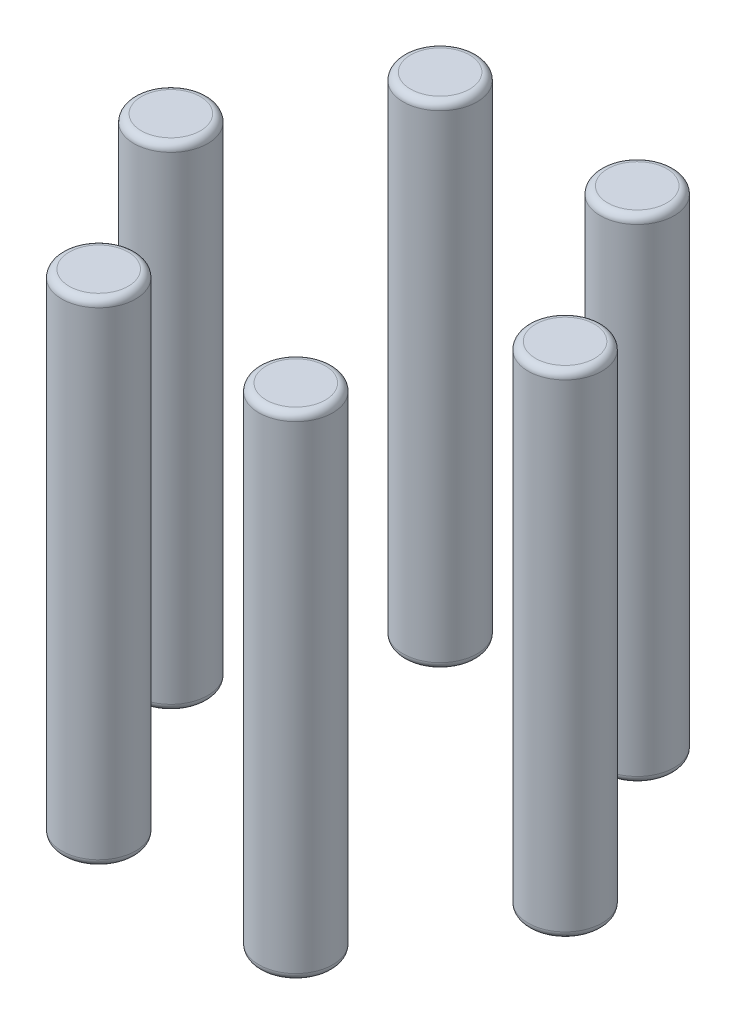
SolidWorks part; units mm, degrees
ref_plane "Front Plane" through (0, 0, 0) normal (0, 0, 1) x (1, 0, 0)
ref_plane "Top Plane" through (0, 0, 0) normal (0, 1, 0) x (1, 0, 0)
ref_plane "Right Plane" through (0, 0, 0) normal (1, 0, 0) x (0, 0, -1)
sketch "Sketch1" plane through (0, 0, 0) normal (0, 1, 0) x (1, 0, 0)
  line L0 (-15.4, 0) -> (14.4, 0) construction
  line L1 (0, 0) -> (0, -14.9128) construction
  line L2 (0, 0) -> (0, 14.9128) construction
  line L3 (-0.5, 0) -> (-0.5, -14.9128) construction
  line L4 (-0.5, 0) -> (-0.5, 14.9128) construction
  line L5 (14.4, 0) -> (15.5, 0) construction
  line L6 (0, 14.9128) -> (0, -14.9128) construction
  line L7 (5.9, 0) -> (9.1, 0) construction
  line L8 (5.9, 0) -> (7.5, 0)
  circle A0 centre (-0.5, 0) radius 16 construction
  circle A1 centre (15.5, 0) radius 1
  circle A2 centre (15.0351, -3.8291) radius 1
  circle A3 centre (13.6673, -7.4356) radius 1
  circle A4 centre (11.4762, -10.61) radius 1
  circle A5 centre (8.589, -13.1677) radius 1
  circle A6 centre (5.1737, -14.9603) radius 1
  circle A7 centre (1.4286, -15.8833) radius 1
  circle A8 centre (-2.4286, -15.8833) radius 1
  circle A9 centre (-6.1737, -14.9603) radius 1
  circle A10 centre (-9.589, -13.1677) radius 1
  circle A11 centre (-12.4762, -10.61) radius 1
  circle A12 centre (-14.6673, -7.4356) radius 1
  circle A13 centre (-16.0351, -3.8291) radius 1
  circle A14 centre (-16.5, 0) radius 1
  circle A15 centre (-16.0351, 3.8291) radius 1
  circle A16 centre (-14.6673, 7.4356) radius 1
  circle A17 centre (-12.4762, 10.61) radius 1
  circle A18 centre (-9.589, 13.1677) radius 1
  circle A19 centre (-6.1737, 14.9603) radius 1
  circle A20 centre (-2.4286, 15.8833) radius 1
  circle A21 centre (1.4286, 15.8833) radius 1
  circle A22 centre (5.1737, 14.9603) radius 1
  circle A23 centre (8.589, 13.1677) radius 1
  circle A24 centre (11.4762, 10.61) radius 1
  circle A25 centre (13.6673, 7.4356) radius 1
  circle A26 centre (15.0351, 3.8291) radius 1
  circle A27 centre (0, 0) radius 8
  circle A28 centre (8, 0) radius 2.1
  circle A29 centre (4, 6.9282) radius 2.1
  circle A30 centre (-4, 6.9282) radius 2.1
  circle A31 centre (-8, 0) radius 2.1
  circle A32 centre (-4, -6.9282) radius 2.1
  circle A33 centre (4, -6.9282) radius 2.1
  circle A34 centre (-1, 0) radius 8 construction
  circle A35 centre (3, -6.9282) radius 2.1
  circle A36 centre (-5, -6.9282) radius 2.1
  circle A37 centre (-9, 0) radius 2.1
  circle A38 centre (-5, 6.9282) radius 2.1
  circle A39 centre (3, 6.9282) radius 2.1
  circle A40 centre (7, 0) radius 2.1
  circle A41 centre (7.5, 0) radius 1.5
  circle A42 centre (3.5, -6.9282) radius 1.5
  circle A43 centre (-4.5, -6.9282) radius 1.5
  circle A44 centre (-8.5, 0) radius 1.5
  circle A45 centre (-4.5, 6.9282) radius 1.5
  circle A46 centre (3.5, 6.9282) radius 1.5
  spline S0 degree 4 poles (14.1521, 3.1658) (14.188, 3.1199) (14.2658, 3.0332) (14.3775, 2.9384) (14.515, 2.8555) (14.6203, 2.806) (14.6874, 2.778) (14.7412, 2.7556) (14.7939, 2.7309) (14.8442, 2.7016) (14.9616, 2.6171) (15.116, 2.4418) (15.2531, 2.163) (15.3044, 1.8261) (15.2781, 1.5454) (15.2134, 1.3341) (15.1457, 1.199) (15.0717, 1.0959) (14.999, 1.0246) (14.9346, 0.9749) (14.8529, 0.9144) (14.7598, 0.8351) (14.6613, 0.7318) (14.5658, 0.5985) (14.4899, 0.4547) (14.4445, 0.3242) (14.4198, 0.2202) (14.4058, 0.1237) (14.3997, 0.036) (14.399, -0.0233) (14.4055, -0.1232) (14.4175, -0.2057) (14.4353, -0.2848) (14.4589, -0.3638) (14.4955, -0.4601) (14.5538, -0.5777) (14.629, -0.6905) (14.7205, -0.7952) (14.8099, -0.8785) (14.886, -0.9397) (14.9653, -0.9969) (15.0394, -1.0608) (15.1018, -1.1365) (15.1543, -1.2193) (15.2086, -1.3292) (15.2563, -1.4688) (15.2881, -1.6381) (15.2945, -1.881) (15.2523, -2.1199) (15.1638, -2.3444) (15.0424, -2.5231) (14.9425, -2.6287) (14.8453, -2.7036) (14.7572, -2.7504) (14.6644, -2.7867) (14.5734, -2.827) (14.4636, -2.8857) (14.309, -2.9902) (14.1305, -3.1658) (13.9721, -3.435) (13.894, -3.7733) (13.9169, -4.0803) (13.9952, -4.3102) (14.0824, -4.4685) (14.1503, -4.5677) (14.21, -4.6429) (14.2706, -4.7176) (14.3202, -4.8002) (14.3654, -4.9109) (14.3993, -5.0496) (14.4169, -5.2624) (14.3843, -5.5009) (14.3041, -5.731) (14.178, -5.9418) (14.0479, -6.0957) (13.9108, -6.2086) (13.7771, -6.2844) (13.6546, -6.3259) (13.5506, -6.3413) (13.4467, -6.3556) (13.3441, -6.3782) (13.2186, -6.4164) (13.0491, -6.4902) (12.8504, -6.6239) (12.6494, -6.8484) (12.5061, -7.1523) (12.463, -7.451) (12.49, -7.6921) (12.5392, -7.8624) (12.5803, -7.968) (12.6183, -8.0504) (12.6544, -8.1336) (12.6783, -8.2214) (12.6929, -8.336) (12.6907, -8.4762) (12.6543, -8.6855) (12.5452, -8.9512) (12.3731, -9.1837) (12.1492, -9.3663) (11.9533, -9.4633) (11.8116, -9.5062) (11.6867, -9.5225) (11.5835, -9.517) (11.4812, -9.5034) (11.3782, -9.4969) (11.2749, -9.4982) (11.1721, -9.508) (11.0085, -9.5382) (10.791, -9.6158) (10.5438, -9.7787) (10.3474, -10.0243) (10.2402, -10.2686) (10.1943, -10.4842) (10.1853, -10.6384) (10.1931, -10.7705) (10.2091, -10.8795) (10.2256, -10.9662) (10.236, -11.0539) (10.2331, -11.1423) (10.2158, -11.2534) (10.1767, -11.3842) (10.0886, -11.5718) (9.9146, -11.8006) (9.6439, -12.0158) (9.3384, -12.1314) (9.0923, -12.1519) (8.9388, -12.1247) (8.8741, -12.1049) (8.8233, -12.0863) (8.76, -12.0622) (8.6577, -12.0268) (8.5127, -11.9913) (8.2954, -11.971) (8.0233, -12.0058) (7.7397, -12.12) (7.4775, -12.3303) (7.3093, -12.5758) (7.2277, -12.7964) (7.1948, -12.9647) (7.1831, -13.0729) (7.1774, -13.16) (7.1639, -13.2682) (7.1207, -13.3961) (7.0432, -13.5357) (6.8963, -13.7154) (6.6678, -13.8963) (6.3478, -14.0387) (6.02, -14.0727) (5.7619, -14.0269) (5.5985, -13.9438) (5.5126, -13.8801) (5.4018, -13.8057) (5.2599, -13.7303) (5.0524, -13.6565) (4.7738, -13.623) (4.4626, -13.6683) (4.1888, -13.7999) (3.9912, -13.9665) (3.8578, -14.1339) (3.7826, -14.2632) (3.7309, -14.3799) (3.6959, -14.48) (3.6689, -14.5606) (3.6251, -14.6573) (3.5494, -14.7647) (3.44, -14.8752) (3.2557, -15.006) (2.9928, -15.1201) (2.6515, -15.1757) (2.3406, -15.1291) (2.1258, -15.0338) (2.011, -14.9468) (1.9698, -14.909) (1.9317, -14.8681) (1.8954, -14.8255) (1.8499, -14.7726) (1.7735, -14.691) (1.6576, -14.5893) (1.4677, -14.4687) (1.2013, -14.3748) (0.8943, -14.3518) (0.5705, -14.4236) (0.3173, -14.5632) (0.1515, -14.7141) (0.0481, -14.8418) (-0.0114, -14.9289) (-0.057, -15.0001) (-0.1205, -15.0845) (-0.2167, -15.1711) (-0.3455, -15.2521) (-0.5484, -15.3356) (-0.8128, -15.3854) (-1.084, -15.3726) (-1.345, -15.2972) (-1.5435, -15.1922) (-1.6658, -15.0976) (-1.7547, -15.002) (-1.8112, -14.9128) (-1.8483, -14.8369) (-1.8948, -14.7422) (-1.9811, -14.5964) (-2.1305, -14.4153) (-2.3717, -14.2374) (-2.6941, -14.1243) (-3.0058, -14.1121) (-3.2798, -14.1742) (-3.4814, -14.2713) (-3.6077, -14.3581) (-3.6929, -14.4296) (-3.7443, -14.4763) (-3.7855, -14.5136) (-3.839, -14.5578) (-3.9718, -14.6426) (-4.2092, -14.7163) (-4.5379, -14.7232) (-4.871, -14.6233) (-5.1192, -14.4741) (-5.2872, -14.3161) (-5.3818, -14.1888) (-5.4416, -14.0686) (-5.4698, -13.9639) (-5.4862, -13.8788) (-5.5106, -13.7734) (-5.5628, -13.6112) (-5.6686, -13.4029) (-5.8615, -13.1808) (-6.1409, -13.0036) (-6.4324, -12.9205) (-6.707, -12.9139) (-6.9246, -12.958) (-7.0705, -13.0119) (-7.1719, -13.0612) (-7.2342, -13.0943) (-7.2842, -13.1203) (-7.3485, -13.1494) (-7.4504, -13.1813) (-7.5929, -13.1993) (-7.8225, -13.1875) (-8.1082, -13.1019) (-8.3607, -12.9481) (-8.5641, -12.7393) (-8.6869, -12.541) (-8.7459, -12.3913) (-8.7711, -12.2579) (-8.7697, -12.1482) (-8.7645, -12.0606) (-8.7633, -11.951) (-8.7731, -11.8212) (-8.8019, -11.6732) (-8.8729, -11.4717) (-9.0045, -11.25) (-9.2205, -11.0351) (-9.4997, -10.8905) (-9.7475, -10.8369) (-9.9383, -10.8322) (-10.0675, -10.8437) (-10.1698, -10.8609) (-10.2704, -10.8859) (-10.3717, -10.9089) (-10.4995, -10.9144) (-10.6499, -10.893) (-10.8644, -10.8236) (-11.1154, -10.6702) (-11.3185, -10.4608) (-11.4614, -10.2119) (-11.5248, -10.0134) (-11.5464, -9.8777) (-11.5487, -9.7646) (-11.5393, -9.6761) (-11.5169, -9.5902) (-11.4896, -9.5058) (-11.4606, -9.3988) (-11.4371, -9.2678) (-11.428, -9.1126) (-11.4489, -8.8917) (-11.5253, -8.6444) (-11.6806, -8.3917) (-11.9083, -8.1893) (-12.1461, -8.0664) (-12.3515, -8.0112) (-12.509, -7.9918) (-12.6408, -7.9895) (-12.7466, -7.9882) (-12.8744, -7.9638) (-13.0178, -7.9059) (-13.1692, -7.8114) (-13.319, -7.6747) (-13.472, -7.4805) (-13.5815, -7.2609) (-13.644, -7.0266) (-13.6529, -6.8129) (-13.6365, -6.6729) (-13.6064, -6.5605) (-13.5704, -6.4764) (-13.5232, -6.3982) (-13.4752, -6.3206) (-13.4215, -6.2199) (-13.3522, -6.0556) (-13.2972, -5.8178) (-13.3061, -5.5112) (-13.4183, -5.1858) (-13.5996, -4.9373) (-13.7884, -4.7826) (-13.9504, -4.6931) (-14.068, -4.6441) (-14.1647, -4.6121) (-14.2634, -4.587) (-14.3606, -4.5562) (-14.4721, -4.4972) (-14.5906, -4.4054) (-14.7415, -4.2409) (-14.8856, -3.984) (-14.9605, -3.7) (-14.9625, -3.4094) (-14.9171, -3.1994) (-14.8649, -3.0656) (-14.8048, -2.9613) (-14.7437, -2.886) (-14.6735, -2.8194) (-14.6048, -2.7515) (-14.5411, -2.6786) (-14.4829, -2.6013) (-14.3984, -2.4684) (-14.3099, -2.2678) (-14.2572, -1.9916) (-14.2948, -1.6527) (-14.4157, -1.3725) (-14.5648, -1.1806) (-14.7009, -1.0585) (-14.8015, -0.9857) (-14.886, -0.9336) (-14.9732, -0.8861) (-15.056, -0.8309) (-15.1453, -0.7457) (-15.2341, -0.6279) (-15.3021, -0.4979) (-15.3506, -0.3595) (-15.3784, -0.2422) (-15.3932, -0.1473) (-15.4005, -0.038) (-15.4007, 0.0312) (-15.3943, 0.133) (-15.3819, 0.2227) (-15.3632, 0.3082) (-15.3383, 0.3938) (-15.2991, 0.498) (-15.241, 0.614) (-15.1569, 0.7356) (-15.0521, 0.8388) (-14.947, 0.9) (-14.8417, 0.9596) (-14.7374, 1.0292) (-14.6222, 1.1253) (-14.4762, 1.2888) (-14.3483, 1.5104) (-14.2696, 1.788) (-14.2718, 2.0824) (-14.3338, 2.3297) (-14.4228, 2.5131) (-14.5089, 2.6398) (-14.5912, 2.7371) (-14.6628, 2.8095) (-14.7315, 2.8736) (-14.7874, 2.9388) (-14.8392, 3.0187) (-14.9, 3.1445) (-14.933, 3.2628) (-14.9484, 3.3663) (-14.9531, 3.4358) knots 0 0 0 0 0 0.003662 0.007324 0.009155 0.010071 0.010986 0.011902 0.012818 0.013733 0.014649 0.020984 0.02732 0.032959 0.035778 0.038598 0.041156 0.042436 0.043715 0.044995 0.046274 0.048833 0.051398 0.053964 0.05653 0.059096 0.059963 0.060831 0.062566 0.06386 0.065154 0.066448 0.067743 0.069037 0.070331 0.072919 0.075992 0.077529 0.079065 0.080602 0.082139 0.083675 0.085212 0.086754 0.088296 0.09138 0.094464 0.097548 0.103529 0.106519 0.10951 0.111075 0.112641 0.114207 0.115773 0.117339 0.118905 0.122036 0.127492 0.132948 0.138255 0.143562 0.146585 0.148096 0.149608 0.151119 0.15263 0.154142 0.155653 0.158618 0.161583 0.167513 0.170668 0.173824 0.176979 0.180135 0.181785 0.183435 0.185086 0.186736 0.188387 0.190037 0.193338 0.198334 0.203329 0.208757 0.214186 0.217039 0.218465 0.219892 0.221319 0.222745 0.224172 0.225598 0.228568 0.231538 0.237477 0.243509 0.246525 0.249541 0.251164 0.252787 0.25441 0.256033 0.257656 0.259279 0.260902 0.262525 0.268116 0.273708 0.279232 0.281995 0.284757 0.287531 0.288919 0.290306 0.291693 0.293081 0.294468 0.295855 0.298752 0.301648 0.307441 0.313806 0.320171 0.321875 0.322726 0.323578 0.32443 0.325282 0.326985 0.330392 0.333799 0.338942 0.344084 0.349371 0.354658 0.3574 0.358771 0.360142 0.361513 0.362884 0.365627 0.368572 0.371516 0.377406 0.383828 0.390249 0.39193 0.393611 0.395291 0.396972 0.400333 0.403695 0.409076 0.414457 0.419833 0.422521 0.425209 0.427878 0.429213 0.430548 0.431883 0.433218 0.435887 0.438758 0.441629 0.44737 0.453781 0.460191 0.46107 0.46195 0.462829 0.463708 0.464587 0.465466 0.467225 0.470742 0.474259 0.479542 0.484825 0.489836 0.494847 0.497504 0.498832 0.500161 0.501489 0.502818 0.505475 0.508247 0.51102 0.516564 0.52227 0.525123 0.527976 0.530631 0.531959 0.533286 0.534614 0.535941 0.538597 0.543936 0.549276 0.554531 0.559787 0.563284 0.566782 0.568531 0.569405 0.570279 0.571154 0.572028 0.573777 0.580153 0.586529 0.592383 0.595311 0.598238 0.600963 0.602326 0.603688 0.605051 0.606414 0.609139 0.614393 0.619646 0.62466 0.629675 0.633224 0.636772 0.638547 0.639434 0.640321 0.641208 0.642095 0.64387 0.647026 0.650182 0.656494 0.66242 0.665383 0.668345 0.671105 0.672484 0.673864 0.675243 0.676623 0.679382 0.682041 0.684701 0.690021 0.695473 0.700926 0.704188 0.705819 0.70745 0.709081 0.710712 0.712344 0.713975 0.717095 0.720216 0.726458 0.732287 0.735201 0.738116 0.739511 0.740907 0.742302 0.743698 0.745093 0.746488 0.749279 0.752059 0.754839 0.760398 0.765424 0.770449 0.773769 0.777088 0.778748 0.780408 0.782068 0.783727 0.786901 0.790075 0.793249 0.796422 0.802397 0.805385 0.808372 0.809808 0.811244 0.812679 0.814115 0.81555 0.816986 0.819857 0.825318 0.830779 0.83599 0.841201 0.844404 0.846006 0.847607 0.849209 0.850811 0.852412 0.854014 0.857107 0.8602 0.866387 0.872353 0.875336 0.878319 0.87984 0.881361 0.882882 0.884402 0.885923 0.887444 0.888965 0.890486 0.895823 0.90116 0.906397 0.911634 0.914757 0.916319 0.91788 0.919441 0.921003 0.922564 0.924126 0.927182 0.930238 0.931767 0.933295 0.934823 0.936351 0.937751 0.93915 0.940549 0.941949 0.943348 0.944747 0.947546 0.950087 0.952628 0.953898 0.955168 0.957709 0.960509 0.96331 0.96891 0.973663 0.978415 0.981621 0.984826 0.986428 0.988031 0.989634 0.991236 0.992332 0.993427 0.995618 1 1 1 1 1 construction
  spline S1 degree 4 poles (14.4, 0) (14.4, -0.018) (14.401, -0.0542) (14.4055, -0.1232) (14.4175, -0.2057) (14.4353, -0.2848) (14.4589, -0.3638) (14.4955, -0.4601) (14.5538, -0.5777) (14.629, -0.6905) (14.7205, -0.7952) (14.8099, -0.8785) (14.886, -0.9397) (14.9653, -0.9969) (15.0394, -1.0608) (15.1018, -1.1365) (15.1543, -1.2193) (15.2086, -1.3292) (15.2563, -1.4688) (15.2881, -1.6381) (15.2945, -1.881) (15.2523, -2.1199) (15.1638, -2.3444) (15.0424, -2.5231) (14.9425, -2.6287) (14.8453, -2.7036) (14.7572, -2.7504) (14.6644, -2.7867) (14.5734, -2.827) (14.4636, -2.8857) (14.309, -2.9902) (14.1305, -3.1658) (13.9721, -3.435) (13.894, -3.7733) (13.9169, -4.0803) (13.9952, -4.3102) (14.0824, -4.4685) (14.1503, -4.5677) (14.21, -4.6429) (14.2706, -4.7176) (14.3202, -4.8002) (14.3654, -4.9109) (14.3993, -5.0496) (14.4169, -5.2624) (14.3843, -5.5009) (14.3041, -5.731) (14.178, -5.9418) (14.0479, -6.0957) (13.9108, -6.2086) (13.7771, -6.2844) (13.6546, -6.3259) (13.5506, -6.3413) (13.4467, -6.3556) (13.3441, -6.3782) (13.2186, -6.4164) (13.0491, -6.4902) (12.8504, -6.6239) (12.6494, -6.8484) (12.5061, -7.1523) (12.463, -7.451) (12.49, -7.6921) (12.5392, -7.8624) (12.5803, -7.968) (12.6183, -8.0504) (12.6544, -8.1336) (12.6783, -8.2214) (12.6929, -8.336) (12.6907, -8.4762) (12.6543, -8.6855) (12.5452, -8.9512) (12.3731, -9.1837) (12.1492, -9.3663) (11.9533, -9.4633) (11.8116, -9.5062) (11.6867, -9.5225) (11.5835, -9.517) (11.4812, -9.5034) (11.3782, -9.4969) (11.2749, -9.4982) (11.1721, -9.508) (11.0085, -9.5382) (10.791, -9.6158) (10.5438, -9.7787) (10.3474, -10.0243) (10.2402, -10.2686) (10.1943, -10.4842) (10.1853, -10.6384) (10.1931, -10.7705) (10.2091, -10.8795) (10.2256, -10.9662) (10.236, -11.0539) (10.2331, -11.1423) (10.2158, -11.2534) (10.1767, -11.3842) (10.0886, -11.5718) (9.9146, -11.8006) (9.6439, -12.0158) (9.3384, -12.1314) (9.0923, -12.1519) (8.9388, -12.1247) (8.8741, -12.1049) (8.8233, -12.0863) (8.76, -12.0622) (8.6577, -12.0268) (8.5127, -11.9913) (8.2954, -11.971) (8.0233, -12.0058) (7.7397, -12.12) (7.4775, -12.3303) (7.3093, -12.5758) (7.2277, -12.7964) (7.1948, -12.9647) (7.1831, -13.0729) (7.1774, -13.16) (7.1639, -13.2682) (7.1207, -13.3961) (7.0432, -13.5357) (6.8963, -13.7154) (6.6678, -13.8963) (6.3478, -14.0387) (6.02, -14.0727) (5.7619, -14.0269) (5.5985, -13.9438) (5.5126, -13.8801) (5.4018, -13.8057) (5.2599, -13.7303) (5.0524, -13.6565) (4.7738, -13.623) (4.4626, -13.6683) (4.1888, -13.7999) (3.9912, -13.9665) (3.8578, -14.1339) (3.7826, -14.2632) (3.7309, -14.3799) (3.6959, -14.48) (3.6689, -14.5606) (3.6251, -14.6573) (3.5494, -14.7647) (3.44, -14.8752) (3.2557, -15.006) (2.9928, -15.1201) (2.6515, -15.1757) (2.3406, -15.1291) (2.1258, -15.0338) (2.011, -14.9468) (1.9698, -14.909) (1.9317, -14.8681) (1.8954, -14.8255) (1.8499, -14.7726) (1.7735, -14.691) (1.6576, -14.5893) (1.4677, -14.4687) (1.2013, -14.3748) (0.8943, -14.3518) (0.5705, -14.4236) (0.3173, -14.5632) (0.1515, -14.7141) (0.0481, -14.8418) (-0.0114, -14.9289) (-0.057, -15.0001) (-0.1205, -15.0845) (-0.2167, -15.1711) (-0.3455, -15.2521) (-0.5484, -15.3356) (-0.8128, -15.3854) (-1.084, -15.3726) (-1.345, -15.2972) (-1.5435, -15.1922) (-1.6658, -15.0976) (-1.7547, -15.002) (-1.8112, -14.9128) (-1.8483, -14.8369) (-1.8948, -14.7422) (-1.9811, -14.5964) (-2.1305, -14.4153) (-2.3717, -14.2374) (-2.6941, -14.1243) (-3.0058, -14.1121) (-3.2798, -14.1742) (-3.4814, -14.2713) (-3.6077, -14.3581) (-3.6929, -14.4296) (-3.7443, -14.4763) (-3.7855, -14.5136) (-3.839, -14.5578) (-3.9718, -14.6426) (-4.2092, -14.7163) (-4.5379, -14.7232) (-4.871, -14.6233) (-5.1192, -14.4741) (-5.2872, -14.3161) (-5.3818, -14.1888) (-5.4416, -14.0686) (-5.4698, -13.9639) (-5.4862, -13.8788) (-5.5106, -13.7734) (-5.5628, -13.6112) (-5.6686, -13.4029) (-5.8615, -13.1808) (-6.1409, -13.0036) (-6.4324, -12.9205) (-6.707, -12.9139) (-6.9246, -12.958) (-7.0705, -13.0119) (-7.1719, -13.0612) (-7.2342, -13.0943) (-7.2842, -13.1203) (-7.3485, -13.1494) (-7.4504, -13.1813) (-7.5929, -13.1993) (-7.8225, -13.1875) (-8.1082, -13.1019) (-8.3607, -12.9481) (-8.5641, -12.7393) (-8.6869, -12.541) (-8.7459, -12.3913) (-8.7711, -12.2579) (-8.7697, -12.1482) (-8.7645, -12.0606) (-8.7633, -11.951) (-8.7731, -11.8212) (-8.8019, -11.6732) (-8.8729, -11.4717) (-9.0045, -11.25) (-9.2205, -11.0351) (-9.4997, -10.8905) (-9.7475, -10.8369) (-9.9383, -10.8322) (-10.0675, -10.8437) (-10.1698, -10.8609) (-10.2704, -10.8859) (-10.3717, -10.9089) (-10.4995, -10.9144) (-10.6499, -10.893) (-10.8644, -10.8236) (-11.1154, -10.6702) (-11.3185, -10.4608) (-11.4614, -10.2119) (-11.5248, -10.0134) (-11.5464, -9.8777) (-11.5487, -9.7646) (-11.5393, -9.6761) (-11.5169, -9.5902) (-11.4896, -9.5058) (-11.4606, -9.3988) (-11.4371, -9.2678) (-11.428, -9.1126) (-11.4489, -8.8917) (-11.5253, -8.6444) (-11.6806, -8.3917) (-11.9083, -8.1893) (-12.1461, -8.0664) (-12.3515, -8.0112) (-12.509, -7.9918) (-12.6408, -7.9895) (-12.7466, -7.9882) (-12.8744, -7.9638) (-13.0178, -7.9059) (-13.1692, -7.8114) (-13.319, -7.6747) (-13.472, -7.4805) (-13.5815, -7.2609) (-13.644, -7.0266) (-13.6529, -6.8129) (-13.6365, -6.6729) (-13.6064, -6.5605) (-13.5704, -6.4764) (-13.5232, -6.3982) (-13.4752, -6.3206) (-13.4215, -6.2199) (-13.3522, -6.0556) (-13.2972, -5.8178) (-13.3061, -5.5112) (-13.4183, -5.1858) (-13.5996, -4.9373) (-13.7884, -4.7826) (-13.9504, -4.6931) (-14.068, -4.6441) (-14.1647, -4.6121) (-14.2634, -4.587) (-14.3606, -4.5562) (-14.4721, -4.4972) (-14.5906, -4.4054) (-14.7415, -4.2409) (-14.8856, -3.984) (-14.9605, -3.7) (-14.9625, -3.4094) (-14.9171, -3.1994) (-14.8649, -3.0656) (-14.8048, -2.9613) (-14.7437, -2.886) (-14.6735, -2.8194) (-14.6048, -2.7515) (-14.5411, -2.6786) (-14.4829, -2.6013) (-14.3984, -2.4684) (-14.3099, -2.2678) (-14.2572, -1.9916) (-14.2948, -1.6527) (-14.4157, -1.3725) (-14.5648, -1.1806) (-14.7009, -1.0585) (-14.8015, -0.9857) (-14.886, -0.9336) (-14.9732, -0.8861) (-15.056, -0.8309) (-15.1453, -0.7457) (-15.2341, -0.6279) (-15.3021, -0.4979) (-15.3506, -0.3595) (-15.3784, -0.2422) (-15.3932, -0.1473) (-15.3988, -0.0635) (-15.4, -0.0212) (-15.4, 0) knots 0.062566 0.062566 0.062566 0.062566 0.062566 0.06386 0.065154 0.066448 0.067743 0.069037 0.070331 0.072919 0.075992 0.077529 0.079065 0.080602 0.082139 0.083675 0.085212 0.086754 0.088296 0.09138 0.094464 0.097548 0.103529 0.106519 0.10951 0.111075 0.112641 0.114207 0.115773 0.117339 0.118905 0.122036 0.127492 0.132948 0.138255 0.143562 0.146585 0.148096 0.149608 0.151119 0.15263 0.154142 0.155653 0.158618 0.161583 0.167513 0.170668 0.173824 0.176979 0.180135 0.181785 0.183435 0.185086 0.186736 0.188387 0.190037 0.193338 0.198334 0.203329 0.208757 0.214186 0.217039 0.218465 0.219892 0.221319 0.222745 0.224172 0.225598 0.228568 0.231538 0.237477 0.243509 0.246525 0.249541 0.251164 0.252787 0.25441 0.256033 0.257656 0.259279 0.260902 0.262525 0.268116 0.273708 0.279232 0.281995 0.284757 0.287531 0.288919 0.290306 0.291693 0.293081 0.294468 0.295855 0.298752 0.301648 0.307441 0.313806 0.320171 0.321875 0.322726 0.323578 0.32443 0.325282 0.326985 0.330392 0.333799 0.338942 0.344084 0.349371 0.354658 0.3574 0.358771 0.360142 0.361513 0.362884 0.365627 0.368572 0.371516 0.377406 0.383828 0.390249 0.39193 0.393611 0.395291 0.396972 0.400333 0.403695 0.409076 0.414457 0.419833 0.422521 0.425209 0.427878 0.429213 0.430548 0.431883 0.433218 0.435887 0.438758 0.441629 0.44737 0.453781 0.460191 0.46107 0.46195 0.462829 0.463708 0.464587 0.465466 0.467225 0.470742 0.474259 0.479542 0.484825 0.489836 0.494847 0.497504 0.498832 0.500161 0.501489 0.502818 0.505475 0.508247 0.51102 0.516564 0.52227 0.525123 0.527976 0.530631 0.531959 0.533286 0.534614 0.535941 0.538597 0.543936 0.549276 0.554531 0.559787 0.563284 0.566782 0.568531 0.569405 0.570279 0.571154 0.572028 0.573777 0.580153 0.586529 0.592383 0.595311 0.598238 0.600963 0.602326 0.603688 0.605051 0.606414 0.609139 0.614393 0.619646 0.62466 0.629675 0.633224 0.636772 0.638547 0.639434 0.640321 0.641208 0.642095 0.64387 0.647026 0.650182 0.656494 0.66242 0.665383 0.668345 0.671105 0.672484 0.673864 0.675243 0.676623 0.679382 0.682041 0.684701 0.690021 0.695473 0.700926 0.704188 0.705819 0.70745 0.709081 0.710712 0.712344 0.713975 0.717095 0.720216 0.726458 0.732287 0.735201 0.738116 0.739511 0.740907 0.742302 0.743698 0.745093 0.746488 0.749279 0.752059 0.754839 0.760398 0.765424 0.770449 0.773769 0.777088 0.778748 0.780408 0.782068 0.783727 0.786901 0.790075 0.793249 0.796422 0.802397 0.805385 0.808372 0.809808 0.811244 0.812679 0.814115 0.81555 0.816986 0.819857 0.825318 0.830779 0.83599 0.841201 0.844404 0.846006 0.847607 0.849209 0.850811 0.852412 0.854014 0.857107 0.8602 0.866387 0.872353 0.875336 0.878319 0.87984 0.881361 0.882882 0.884402 0.885923 0.887444 0.888965 0.890486 0.895823 0.90116 0.906397 0.911634 0.914757 0.916319 0.91788 0.919441 0.921003 0.922564 0.924126 0.927182 0.930238 0.931767 0.933295 0.934823 0.936351 0.936351 0.936351 0.936351 0.936351
  spline S2 degree 4 poles (14.4, 0) (14.4, 0.018) (14.401, 0.0542) (14.4055, 0.1232) (14.4175, 0.2057) (14.4353, 0.2848) (14.4589, 0.3638) (14.4955, 0.4601) (14.5538, 0.5777) (14.629, 0.6905) (14.7205, 0.7952) (14.8099, 0.8785) (14.886, 0.9397) (14.9653, 0.9969) (15.0394, 1.0608) (15.1018, 1.1365) (15.1543, 1.2193) (15.2086, 1.3292) (15.2563, 1.4688) (15.2881, 1.6381) (15.2945, 1.881) (15.2523, 2.1199) (15.1638, 2.3444) (15.0424, 2.5231) (14.9425, 2.6287) (14.8453, 2.7036) (14.7572, 2.7504) (14.6644, 2.7867) (14.5734, 2.827) (14.4636, 2.8857) (14.309, 2.9902) (14.1305, 3.1658) (13.9721, 3.435) (13.894, 3.7733) (13.9169, 4.0803) (13.9952, 4.3102) (14.0824, 4.4685) (14.1503, 4.5677) (14.21, 4.6429) (14.2706, 4.7176) (14.3202, 4.8002) (14.3654, 4.9109) (14.3993, 5.0496) (14.4169, 5.2624) (14.3843, 5.5009) (14.3041, 5.731) (14.178, 5.9418) (14.0479, 6.0957) (13.9108, 6.2086) (13.7771, 6.2844) (13.6546, 6.3259) (13.5506, 6.3413) (13.4467, 6.3556) (13.3441, 6.3782) (13.2186, 6.4164) (13.0491, 6.4902) (12.8504, 6.6239) (12.6494, 6.8484) (12.5061, 7.1523) (12.463, 7.451) (12.49, 7.6921) (12.5392, 7.8624) (12.5803, 7.968) (12.6183, 8.0504) (12.6544, 8.1336) (12.6783, 8.2214) (12.6929, 8.336) (12.6907, 8.4762) (12.6543, 8.6855) (12.5452, 8.9512) (12.3731, 9.1837) (12.1492, 9.3663) (11.9533, 9.4633) (11.8116, 9.5062) (11.6867, 9.5225) (11.5835, 9.517) (11.4812, 9.5034) (11.3782, 9.4969) (11.2749, 9.4982) (11.1721, 9.508) (11.0085, 9.5382) (10.791, 9.6158) (10.5438, 9.7787) (10.3474, 10.0243) (10.2402, 10.2686) (10.1943, 10.4842) (10.1853, 10.6384) (10.1931, 10.7705) (10.2091, 10.8795) (10.2256, 10.9662) (10.236, 11.0539) (10.2331, 11.1423) (10.2158, 11.2534) (10.1767, 11.3842) (10.0886, 11.5718) (9.9146, 11.8006) (9.6439, 12.0158) (9.3384, 12.1314) (9.0923, 12.1519) (8.9388, 12.1247) (8.8741, 12.1049) (8.8233, 12.0863) (8.76, 12.0622) (8.6577, 12.0268) (8.5127, 11.9913) (8.2954, 11.971) (8.0233, 12.0058) (7.7397, 12.12) (7.4775, 12.3303) (7.3093, 12.5758) (7.2277, 12.7964) (7.1948, 12.9647) (7.1831, 13.0729) (7.1774, 13.16) (7.1639, 13.2682) (7.1207, 13.3961) (7.0432, 13.5357) (6.8963, 13.7154) (6.6678, 13.8963) (6.3478, 14.0387) (6.02, 14.0727) (5.7619, 14.0269) (5.5985, 13.9438) (5.5126, 13.8801) (5.4018, 13.8057) (5.2599, 13.7303) (5.0524, 13.6565) (4.7738, 13.623) (4.4626, 13.6683) (4.1888, 13.7999) (3.9912, 13.9665) (3.8578, 14.1339) (3.7826, 14.2632) (3.7309, 14.3799) (3.6959, 14.48) (3.6689, 14.5606) (3.6251, 14.6573) (3.5494, 14.7647) (3.44, 14.8752) (3.2557, 15.006) (2.9928, 15.1201) (2.6515, 15.1757) (2.3406, 15.1291) (2.1258, 15.0338) (2.011, 14.9468) (1.9698, 14.909) (1.9317, 14.8681) (1.8954, 14.8255) (1.8499, 14.7726) (1.7735, 14.691) (1.6576, 14.5893) (1.4677, 14.4687) (1.2013, 14.3748) (0.8943, 14.3518) (0.5705, 14.4236) (0.3173, 14.5632) (0.1515, 14.7141) (0.0481, 14.8418) (-0.0114, 14.9289) (-0.057, 15) (-0.1205, 15.0845) (-0.2167, 15.1711) (-0.3455, 15.2521) (-0.5484, 15.3356) (-0.8128, 15.3854) (-1.084, 15.3726) (-1.345, 15.2972) (-1.5435, 15.1922) (-1.6658, 15.0976) (-1.7547, 15.002) (-1.8112, 14.9128) (-1.8483, 14.8369) (-1.8948, 14.7422) (-1.9811, 14.5964) (-2.1305, 14.4153) (-2.3717, 14.2374) (-2.6941, 14.1243) (-3.0058, 14.1121) (-3.2798, 14.1742) (-3.4814, 14.2713) (-3.6077, 14.3581) (-3.6929, 14.4296) (-3.7443, 14.4763) (-3.7855, 14.5136) (-3.839, 14.5578) (-3.9718, 14.6426) (-4.2092, 14.7163) (-4.5379, 14.7232) (-4.871, 14.6233) (-5.1192, 14.4741) (-5.2872, 14.3161) (-5.3818, 14.1887) (-5.4416, 14.0686) (-5.4698, 13.9639) (-5.4862, 13.8788) (-5.5106, 13.7734) (-5.5628, 13.6112) (-5.6686, 13.4029) (-5.8615, 13.1808) (-6.1409, 13.0036) (-6.4324, 12.9205) (-6.707, 12.9139) (-6.9246, 12.958) (-7.0705, 13.0119) (-7.1719, 13.0612) (-7.2342, 13.0943) (-7.2842, 13.1203) (-7.3485, 13.1494) (-7.4504, 13.1813) (-7.5929, 13.1993) (-7.8225, 13.1875) (-8.1082, 13.1019) (-8.3607, 12.9481) (-8.5641, 12.7393) (-8.6869, 12.541) (-8.7459, 12.3913) (-8.7711, 12.2579) (-8.7697, 12.1482) (-8.7645, 12.0606) (-8.7633, 11.951) (-8.7731, 11.8212) (-8.8019, 11.6732) (-8.8729, 11.4717) (-9.0045, 11.25) (-9.2205, 11.0351) (-9.4997, 10.8905) (-9.7475, 10.8369) (-9.9383, 10.8322) (-10.0675, 10.8437) (-10.1698, 10.8609) (-10.2704, 10.8859) (-10.3717, 10.9089) (-10.4995, 10.9144) (-10.6499, 10.893) (-10.8644, 10.8236) (-11.1154, 10.6702) (-11.3185, 10.4608) (-11.4614, 10.2119) (-11.5248, 10.0134) (-11.5464, 9.8777) (-11.5487, 9.7646) (-11.5393, 9.6761) (-11.5169, 9.5902) (-11.4896, 9.5058) (-11.4606, 9.3988) (-11.4371, 9.2678) (-11.428, 9.1126) (-11.4489, 8.8917) (-11.5253, 8.6444) (-11.6806, 8.3917) (-11.9083, 8.1893) (-12.1461, 8.0664) (-12.3515, 8.0112) (-12.509, 7.9918) (-12.6408, 7.9895) (-12.7466, 7.9882) (-12.8744, 7.9638) (-13.0178, 7.9059) (-13.1692, 7.8114) (-13.319, 7.6747) (-13.472, 7.4805) (-13.5815, 7.2609) (-13.644, 7.0266) (-13.6529, 6.8129) (-13.6365, 6.6728) (-13.6064, 6.5605) (-13.5704, 6.4764) (-13.5232, 6.3982) (-13.4752, 6.3206) (-13.4215, 6.2199) (-13.3522, 6.0556) (-13.2972, 5.8178) (-13.3061, 5.5112) (-13.4183, 5.1858) (-13.5996, 4.9373) (-13.7884, 4.7826) (-13.9504, 4.6931) (-14.068, 4.6441) (-14.1647, 4.6121) (-14.2634, 4.587) (-14.3606, 4.5562) (-14.4721, 4.4972) (-14.5906, 4.4054) (-14.7415, 4.2409) (-14.8856, 3.984) (-14.9605, 3.7) (-14.9625, 3.4094) (-14.9171, 3.1994) (-14.8649, 3.0655) (-14.8048, 2.9613) (-14.7437, 2.886) (-14.6735, 2.8194) (-14.6048, 2.7515) (-14.5411, 2.6786) (-14.4829, 2.6013) (-14.3984, 2.4684) (-14.3099, 2.2678) (-14.2572, 1.9916) (-14.2948, 1.6527) (-14.4157, 1.3725) (-14.5648, 1.1806) (-14.7009, 1.0585) (-14.8015, 0.9857) (-14.886, 0.9336) (-14.9732, 0.8861) (-15.056, 0.8309) (-15.1453, 0.7457) (-15.2341, 0.6279) (-15.3021, 0.4979) (-15.3506, 0.3595) (-15.3784, 0.2422) (-15.3932, 0.1473) (-15.3988, 0.0635) (-15.4, 0.0212) (-15.4, 0) knots 0.062566 0.062566 0.062566 0.062566 0.062566 0.06386 0.065154 0.066448 0.067743 0.069037 0.070331 0.072919 0.075992 0.077529 0.079065 0.080602 0.082139 0.083675 0.085212 0.086754 0.088296 0.09138 0.094464 0.097548 0.103529 0.106519 0.10951 0.111075 0.112641 0.114207 0.115773 0.117339 0.118905 0.122036 0.127492 0.132948 0.138255 0.143562 0.146585 0.148096 0.149608 0.151119 0.15263 0.154142 0.155653 0.158618 0.161583 0.167513 0.170668 0.173824 0.176979 0.180135 0.181785 0.183435 0.185086 0.186736 0.188387 0.190037 0.193338 0.198334 0.203329 0.208757 0.214186 0.217039 0.218465 0.219892 0.221319 0.222745 0.224172 0.225598 0.228568 0.231538 0.237477 0.243509 0.246525 0.249541 0.251164 0.252787 0.25441 0.256033 0.257656 0.259279 0.260902 0.262525 0.268116 0.273708 0.279232 0.281995 0.284757 0.287531 0.288919 0.290306 0.291693 0.293081 0.294468 0.295855 0.298752 0.301648 0.307441 0.313806 0.320171 0.321875 0.322726 0.323578 0.32443 0.325282 0.326985 0.330392 0.333799 0.338942 0.344084 0.349371 0.354658 0.3574 0.358771 0.360142 0.361513 0.362884 0.365627 0.368572 0.371516 0.377406 0.383828 0.390249 0.39193 0.393611 0.395291 0.396972 0.400333 0.403695 0.409076 0.414457 0.419833 0.422521 0.425209 0.427878 0.429213 0.430548 0.431883 0.433218 0.435887 0.438758 0.441629 0.44737 0.453781 0.460191 0.46107 0.46195 0.462829 0.463708 0.464587 0.465466 0.467225 0.470742 0.474259 0.479542 0.484825 0.489836 0.494847 0.497504 0.498832 0.500161 0.501489 0.502818 0.505475 0.508247 0.51102 0.516564 0.52227 0.525123 0.527976 0.530631 0.531959 0.533286 0.534614 0.535941 0.538597 0.543936 0.549276 0.554531 0.559787 0.563284 0.566782 0.568531 0.569405 0.570279 0.571154 0.572028 0.573777 0.580153 0.586529 0.592383 0.595311 0.598238 0.600963 0.602326 0.603688 0.605051 0.606414 0.609139 0.614393 0.619646 0.62466 0.629675 0.633224 0.636772 0.638547 0.639434 0.640321 0.641208 0.642095 0.64387 0.647026 0.650182 0.656494 0.66242 0.665383 0.668345 0.671105 0.672484 0.673864 0.675243 0.676623 0.679382 0.682041 0.684701 0.690021 0.695473 0.700926 0.704188 0.705819 0.70745 0.709081 0.710712 0.712344 0.713975 0.717095 0.720216 0.726458 0.732287 0.735201 0.738116 0.739511 0.740907 0.742302 0.743698 0.745093 0.746488 0.749279 0.752059 0.754839 0.760398 0.765424 0.770449 0.773769 0.777088 0.778748 0.780408 0.782068 0.783727 0.786901 0.790075 0.793249 0.796422 0.802397 0.805385 0.808372 0.809808 0.811244 0.812679 0.814115 0.81555 0.816986 0.819857 0.825318 0.830779 0.83599 0.841201 0.844404 0.846006 0.847607 0.849209 0.850811 0.852412 0.854014 0.857107 0.8602 0.866387 0.872353 0.875336 0.878319 0.87984 0.881361 0.882882 0.884402 0.885923 0.887444 0.888965 0.890486 0.895823 0.90116 0.906397 0.911634 0.914757 0.916319 0.91788 0.919441 0.921003 0.922564 0.924126 0.927182 0.930238 0.931767 0.933295 0.934823 0.936351 0.936351 0.936351 0.936351 0.936351
  spline S3 degree 4 poles (-15.4, 0) (-15.4, -0.018) (-15.401, -0.0542) (-15.4055, -0.1232) (-15.4175, -0.2057) (-15.4353, -0.2848) (-15.4589, -0.3638) (-15.4955, -0.4601) (-15.5538, -0.5777) (-15.629, -0.6905) (-15.7205, -0.7952) (-15.8099, -0.8785) (-15.886, -0.9397) (-15.9653, -0.9969) (-16.0394, -1.0608) (-16.1018, -1.1365) (-16.1543, -1.2193) (-16.2086, -1.3292) (-16.2563, -1.4688) (-16.2881, -1.6381) (-16.2945, -1.881) (-16.2523, -2.1199) (-16.1638, -2.3444) (-16.0424, -2.5231) (-15.9425, -2.6287) (-15.8453, -2.7036) (-15.7572, -2.7504) (-15.6644, -2.7867) (-15.5734, -2.827) (-15.4636, -2.8857) (-15.309, -2.9902) (-15.1305, -3.1658) (-14.9721, -3.435) (-14.894, -3.7733) (-14.9169, -4.0803) (-14.9952, -4.3102) (-15.0824, -4.4685) (-15.1503, -4.5677) (-15.21, -4.6429) (-15.2706, -4.7176) (-15.3202, -4.8002) (-15.3654, -4.9109) (-15.3993, -5.0496) (-15.4169, -5.2624) (-15.3843, -5.5009) (-15.3041, -5.731) (-15.178, -5.9418) (-15.0479, -6.0957) (-14.9108, -6.2086) (-14.7771, -6.2844) (-14.6546, -6.3259) (-14.5506, -6.3413) (-14.4467, -6.3556) (-14.3441, -6.3782) (-14.2186, -6.4164) (-14.0491, -6.4902) (-13.8504, -6.6239) (-13.6494, -6.8484) (-13.5061, -7.1523) (-13.463, -7.451) (-13.49, -7.6921) (-13.5392, -7.8624) (-13.5803, -7.968) (-13.6183, -8.0504) (-13.6544, -8.1336) (-13.6783, -8.2214) (-13.6929, -8.336) (-13.6907, -8.4762) (-13.6543, -8.6855) (-13.5452, -8.9512) (-13.3731, -9.1837) (-13.1492, -9.3663) (-12.9533, -9.4633) (-12.8116, -9.5062) (-12.6867, -9.5225) (-12.5835, -9.517) (-12.4812, -9.5034) (-12.3782, -9.4969) (-12.2749, -9.4982) (-12.1721, -9.508) (-12.0085, -9.5382) (-11.791, -9.6158) (-11.5438, -9.7787) (-11.3474, -10.0243) (-11.2402, -10.2686) (-11.1943, -10.4842) (-11.1853, -10.6384) (-11.1931, -10.7705) (-11.2091, -10.8795) (-11.2256, -10.9662) (-11.236, -11.0539) (-11.2331, -11.1423) (-11.2158, -11.2534) (-11.1767, -11.3842) (-11.0886, -11.5718) (-10.9146, -11.8006) (-10.6439, -12.0158) (-10.3384, -12.1314) (-10.0923, -12.1519) (-9.9388, -12.1247) (-9.8741, -12.1049) (-9.8233, -12.0863) (-9.76, -12.0622) (-9.6577, -12.0268) (-9.5127, -11.9913) (-9.2954, -11.971) (-9.0233, -12.0058) (-8.7397, -12.12) (-8.4775, -12.3303) (-8.3093, -12.5758) (-8.2277, -12.7964) (-8.1948, -12.9647) (-8.1831, -13.0729) (-8.1774, -13.16) (-8.1639, -13.2682) (-8.1207, -13.3961) (-8.0432, -13.5357) (-7.8963, -13.7154) (-7.6678, -13.8963) (-7.3478, -14.0387) (-7.02, -14.0727) (-6.7619, -14.0269) (-6.5985, -13.9438) (-6.5126, -13.8801) (-6.4018, -13.8057) (-6.2599, -13.7303) (-6.0524, -13.6565) (-5.7738, -13.623) (-5.4626, -13.6683) (-5.1888, -13.7999) (-4.9912, -13.9665) (-4.8578, -14.1339) (-4.7826, -14.2632) (-4.7309, -14.3799) (-4.6959, -14.48) (-4.6689, -14.5606) (-4.6251, -14.6573) (-4.5494, -14.7647) (-4.44, -14.8752) (-4.2557, -15.006) (-3.9928, -15.1201) (-3.6515, -15.1757) (-3.3406, -15.1291) (-3.1258, -15.0338) (-3.011, -14.9468) (-2.9698, -14.909) (-2.9317, -14.8681) (-2.8954, -14.8255) (-2.8499, -14.7726) (-2.7735, -14.691) (-2.6576, -14.5893) (-2.4677, -14.4687) (-2.2013, -14.3748) (-1.8943, -14.3518) (-1.5705, -14.4236) (-1.3173, -14.5632) (-1.1515, -14.7141) (-1.0481, -14.8418) (-0.9886, -14.9289) (-0.943, -15) (-0.8795, -15.0845) (-0.7833, -15.1711) (-0.6545, -15.2521) (-0.4516, -15.3356) (-0.1872, -15.3854) (0.084, -15.3726) (0.345, -15.2972) (0.5435, -15.1922) (0.6658, -15.0976) (0.7547, -15.002) (0.8112, -14.9128) (0.8483, -14.8369) (0.8948, -14.7422) (0.9811, -14.5964) (1.1305, -14.4153) (1.3717, -14.2374) (1.6941, -14.1243) (2.0058, -14.1121) (2.2798, -14.1742) (2.4814, -14.2713) (2.6077, -14.3581) (2.6929, -14.4296) (2.7443, -14.4763) (2.7855, -14.5136) (2.839, -14.5578) (2.9718, -14.6426) (3.2092, -14.7163) (3.5379, -14.7232) (3.871, -14.6233) (4.1192, -14.4741) (4.2872, -14.3161) (4.3818, -14.1887) (4.4416, -14.0686) (4.4698, -13.9639) (4.4862, -13.8788) (4.5106, -13.7734) (4.5628, -13.6112) (4.6686, -13.4029) (4.8615, -13.1808) (5.1409, -13.0036) (5.4324, -12.9205) (5.707, -12.9139) (5.9246, -12.958) (6.0705, -13.0119) (6.1719, -13.0612) (6.2342, -13.0943) (6.2842, -13.1203) (6.3485, -13.1494) (6.4504, -13.1813) (6.5929, -13.1993) (6.8225, -13.1875) (7.1082, -13.1019) (7.3607, -12.9481) (7.5641, -12.7393) (7.6869, -12.541) (7.7459, -12.3913) (7.7711, -12.2579) (7.7697, -12.1482) (7.7645, -12.0606) (7.7633, -11.951) (7.7731, -11.8212) (7.8019, -11.6732) (7.8729, -11.4717) (8.0045, -11.25) (8.2205, -11.0351) (8.4997, -10.8905) (8.7475, -10.8369) (8.9383, -10.8322) (9.0675, -10.8437) (9.1698, -10.8609) (9.2704, -10.8859) (9.3717, -10.9089) (9.4995, -10.9144) (9.6499, -10.893) (9.8644, -10.8236) (10.1154, -10.6702) (10.3185, -10.4608) (10.4614, -10.2119) (10.5248, -10.0134) (10.5464, -9.8777) (10.5487, -9.7646) (10.5393, -9.6761) (10.5169, -9.5902) (10.4896, -9.5058) (10.4606, -9.3988) (10.4371, -9.2678) (10.428, -9.1126) (10.4489, -8.8917) (10.5253, -8.6444) (10.6806, -8.3917) (10.9083, -8.1893) (11.1461, -8.0664) (11.3515, -8.0112) (11.509, -7.9918) (11.6408, -7.9895) (11.7466, -7.9882) (11.8744, -7.9638) (12.0178, -7.9059) (12.1692, -7.8114) (12.319, -7.6747) (12.472, -7.4805) (12.5815, -7.2609) (12.644, -7.0266) (12.6529, -6.8129) (12.6365, -6.6728) (12.6064, -6.5605) (12.5704, -6.4764) (12.5232, -6.3982) (12.4752, -6.3206) (12.4215, -6.2199) (12.3522, -6.0556) (12.2972, -5.8178) (12.3061, -5.5112) (12.4183, -5.1858) (12.5996, -4.9373) (12.7884, -4.7826) (12.9504, -4.6931) (13.068, -4.6441) (13.1647, -4.6121) (13.2634, -4.587) (13.3606, -4.5562) (13.4721, -4.4972) (13.5906, -4.4054) (13.7415, -4.2409) (13.8856, -3.984) (13.9605, -3.7) (13.9625, -3.4094) (13.9171, -3.1994) (13.8649, -3.0655) (13.8048, -2.9613) (13.7437, -2.886) (13.6735, -2.8194) (13.6048, -2.7515) (13.5411, -2.6786) (13.4829, -2.6013) (13.3984, -2.4684) (13.3099, -2.2678) (13.2572, -1.9916) (13.2948, -1.6527) (13.4157, -1.3725) (13.5648, -1.1806) (13.7009, -1.0585) (13.8015, -0.9857) (13.886, -0.9336) (13.9732, -0.8861) (14.056, -0.8309) (14.1453, -0.7457) (14.2341, -0.6279) (14.3021, -0.4979) (14.3506, -0.3595) (14.3784, -0.2422) (14.3932, -0.1473) (14.3988, -0.0635) (14.4, -0.0212) (14.4, 0) knots 0.062566 0.062566 0.062566 0.062566 0.062566 0.06386 0.065154 0.066448 0.067743 0.069037 0.070331 0.072919 0.075992 0.077529 0.079065 0.080602 0.082139 0.083675 0.085212 0.086754 0.088296 0.09138 0.094464 0.097548 0.103529 0.106519 0.10951 0.111075 0.112641 0.114207 0.115773 0.117339 0.118905 0.122036 0.127492 0.132948 0.138255 0.143562 0.146585 0.148096 0.149608 0.151119 0.15263 0.154142 0.155653 0.158618 0.161583 0.167513 0.170668 0.173824 0.176979 0.180135 0.181785 0.183435 0.185086 0.186736 0.188387 0.190037 0.193338 0.198334 0.203329 0.208757 0.214186 0.217039 0.218465 0.219892 0.221319 0.222745 0.224172 0.225598 0.228568 0.231538 0.237477 0.243509 0.246525 0.249541 0.251164 0.252787 0.25441 0.256033 0.257656 0.259279 0.260902 0.262525 0.268116 0.273708 0.279232 0.281995 0.284757 0.287531 0.288919 0.290306 0.291693 0.293081 0.294468 0.295855 0.298752 0.301648 0.307441 0.313806 0.320171 0.321875 0.322726 0.323578 0.32443 0.325282 0.326985 0.330392 0.333799 0.338942 0.344084 0.349371 0.354658 0.3574 0.358771 0.360142 0.361513 0.362884 0.365627 0.368572 0.371516 0.377406 0.383828 0.390249 0.39193 0.393611 0.395291 0.396972 0.400333 0.403695 0.409076 0.414457 0.419833 0.422521 0.425209 0.427878 0.429213 0.430548 0.431883 0.433218 0.435887 0.438758 0.441629 0.44737 0.453781 0.460191 0.46107 0.46195 0.462829 0.463708 0.464587 0.465466 0.467225 0.470742 0.474259 0.479542 0.484825 0.489836 0.494847 0.497504 0.498832 0.500161 0.501489 0.502818 0.505475 0.508247 0.51102 0.516564 0.52227 0.525123 0.527976 0.530631 0.531959 0.533286 0.534614 0.535941 0.538597 0.543936 0.549276 0.554531 0.559787 0.563284 0.566782 0.568531 0.569405 0.570279 0.571154 0.572028 0.573777 0.580153 0.586529 0.592383 0.595311 0.598238 0.600963 0.602326 0.603688 0.605051 0.606414 0.609139 0.614393 0.619646 0.62466 0.629675 0.633224 0.636772 0.638547 0.639434 0.640321 0.641208 0.642095 0.64387 0.647026 0.650182 0.656494 0.66242 0.665383 0.668345 0.671105 0.672484 0.673864 0.675243 0.676623 0.679382 0.682041 0.684701 0.690021 0.695473 0.700926 0.704188 0.705819 0.70745 0.709081 0.710712 0.712344 0.713975 0.717095 0.720216 0.726458 0.732287 0.735201 0.738116 0.739511 0.740907 0.742302 0.743698 0.745093 0.746488 0.749279 0.752059 0.754839 0.760398 0.765424 0.770449 0.773769 0.777088 0.778748 0.780408 0.782068 0.783727 0.786901 0.790075 0.793249 0.796422 0.802397 0.805385 0.808372 0.809808 0.811244 0.812679 0.814115 0.81555 0.816986 0.819857 0.825318 0.830779 0.83599 0.841201 0.844404 0.846006 0.847607 0.849209 0.850811 0.852412 0.854014 0.857107 0.8602 0.866387 0.872353 0.875336 0.878319 0.87984 0.881361 0.882882 0.884402 0.885923 0.887444 0.888965 0.890486 0.895823 0.90116 0.906397 0.911634 0.914757 0.916319 0.91788 0.919441 0.921003 0.922564 0.924126 0.927182 0.930238 0.931767 0.933295 0.934823 0.936351 0.936351 0.936351 0.936351 0.936351
  spline S4 degree 4 poles (-15.4, 0) (-15.4, 0.018) (-15.401, 0.0542) (-15.4055, 0.1232) (-15.4175, 0.2057) (-15.4353, 0.2848) (-15.4589, 0.3638) (-15.4955, 0.4601) (-15.5538, 0.5777) (-15.629, 0.6905) (-15.7205, 0.7952) (-15.8099, 0.8785) (-15.886, 0.9397) (-15.9653, 0.9969) (-16.0394, 1.0608) (-16.1018, 1.1365) (-16.1543, 1.2193) (-16.2086, 1.3292) (-16.2563, 1.4688) (-16.2881, 1.6381) (-16.2945, 1.881) (-16.2523, 2.1199) (-16.1638, 2.3444) (-16.0424, 2.5231) (-15.9425, 2.6287) (-15.8453, 2.7036) (-15.7572, 2.7504) (-15.6644, 2.7867) (-15.5734, 2.827) (-15.4636, 2.8857) (-15.309, 2.9902) (-15.1305, 3.1658) (-14.9721, 3.435) (-14.894, 3.7733) (-14.9169, 4.0803) (-14.9952, 4.3102) (-15.0824, 4.4685) (-15.1503, 4.5677) (-15.21, 4.6429) (-15.2706, 4.7176) (-15.3202, 4.8002) (-15.3654, 4.9109) (-15.3993, 5.0496) (-15.4169, 5.2624) (-15.3843, 5.5009) (-15.3041, 5.731) (-15.178, 5.9418) (-15.0479, 6.0957) (-14.9108, 6.2086) (-14.7771, 6.2844) (-14.6546, 6.3259) (-14.5506, 6.3413) (-14.4467, 6.3556) (-14.3441, 6.3782) (-14.2186, 6.4164) (-14.0491, 6.4902) (-13.8504, 6.6239) (-13.6494, 6.8484) (-13.5061, 7.1523) (-13.463, 7.451) (-13.49, 7.6921) (-13.5392, 7.8624) (-13.5803, 7.968) (-13.6183, 8.0504) (-13.6544, 8.1336) (-13.6783, 8.2214) (-13.6929, 8.336) (-13.6907, 8.4762) (-13.6543, 8.6855) (-13.5452, 8.9512) (-13.3731, 9.1837) (-13.1492, 9.3663) (-12.9533, 9.4633) (-12.8116, 9.5062) (-12.6867, 9.5225) (-12.5835, 9.517) (-12.4812, 9.5034) (-12.3782, 9.4969) (-12.2749, 9.4982) (-12.1721, 9.508) (-12.0085, 9.5382) (-11.791, 9.6158) (-11.5438, 9.7787) (-11.3474, 10.0243) (-11.2402, 10.2686) (-11.1943, 10.4842) (-11.1853, 10.6384) (-11.1931, 10.7705) (-11.2091, 10.8795) (-11.2256, 10.9662) (-11.236, 11.0539) (-11.2331, 11.1423) (-11.2158, 11.2534) (-11.1767, 11.3842) (-11.0886, 11.5718) (-10.9146, 11.8006) (-10.6439, 12.0158) (-10.3384, 12.1314) (-10.0923, 12.1519) (-9.9388, 12.1247) (-9.8741, 12.1049) (-9.8233, 12.0863) (-9.76, 12.0622) (-9.6577, 12.0268) (-9.5127, 11.9913) (-9.2954, 11.971) (-9.0233, 12.0058) (-8.7397, 12.12) (-8.4775, 12.3303) (-8.3093, 12.5758) (-8.2277, 12.7964) (-8.1948, 12.9647) (-8.1831, 13.0729) (-8.1774, 13.16) (-8.1639, 13.2682) (-8.1207, 13.3961) (-8.0432, 13.5357) (-7.8963, 13.7154) (-7.6678, 13.8963) (-7.3478, 14.0387) (-7.02, 14.0727) (-6.7619, 14.0269) (-6.5985, 13.9438) (-6.5126, 13.8801) (-6.4018, 13.8057) (-6.2599, 13.7303) (-6.0524, 13.6565) (-5.7738, 13.623) (-5.4626, 13.6683) (-5.1888, 13.7999) (-4.9912, 13.9665) (-4.8578, 14.1339) (-4.7826, 14.2632) (-4.7309, 14.3799) (-4.6959, 14.48) (-4.6689, 14.5606) (-4.6251, 14.6573) (-4.5494, 14.7647) (-4.44, 14.8752) (-4.2557, 15.006) (-3.9928, 15.1201) (-3.6515, 15.1757) (-3.3406, 15.1291) (-3.1258, 15.0338) (-3.011, 14.9468) (-2.9698, 14.909) (-2.9317, 14.8681) (-2.8954, 14.8255) (-2.8499, 14.7726) (-2.7735, 14.691) (-2.6576, 14.5893) (-2.4677, 14.4687) (-2.2013, 14.3748) (-1.8943, 14.3518) (-1.5705, 14.4236) (-1.3173, 14.5632) (-1.1515, 14.7141) (-1.0481, 14.8418) (-0.9886, 14.9289) (-0.943, 15) (-0.8795, 15.0845) (-0.7833, 15.1711) (-0.6545, 15.2521) (-0.4516, 15.3356) (-0.1872, 15.3854) (0.084, 15.3726) (0.345, 15.2972) (0.5435, 15.1922) (0.6658, 15.0976) (0.7547, 15.002) (0.8112, 14.9128) (0.8483, 14.8369) (0.8948, 14.7422) (0.9811, 14.5964) (1.1305, 14.4153) (1.3717, 14.2374) (1.6941, 14.1243) (2.0058, 14.1121) (2.2798, 14.1742) (2.4814, 14.2713) (2.6077, 14.3581) (2.6929, 14.4296) (2.7443, 14.4763) (2.7855, 14.5136) (2.839, 14.5578) (2.9718, 14.6426) (3.2092, 14.7163) (3.5379, 14.7232) (3.871, 14.6233) (4.1192, 14.4741) (4.2872, 14.3161) (4.3818, 14.1887) (4.4416, 14.0686) (4.4698, 13.9639) (4.4862, 13.8788) (4.5106, 13.7734) (4.5628, 13.6112) (4.6686, 13.4029) (4.8615, 13.1808) (5.1409, 13.0036) (5.4324, 12.9205) (5.707, 12.9139) (5.9246, 12.958) (6.0705, 13.0119) (6.1719, 13.0612) (6.2342, 13.0943) (6.2842, 13.1203) (6.3485, 13.1494) (6.4504, 13.1813) (6.5929, 13.1993) (6.8225, 13.1875) (7.1082, 13.1019) (7.3607, 12.9481) (7.5641, 12.7393) (7.6869, 12.541) (7.7459, 12.3913) (7.7711, 12.2579) (7.7697, 12.1482) (7.7645, 12.0606) (7.7633, 11.951) (7.7731, 11.8212) (7.8019, 11.6732) (7.8729, 11.4717) (8.0045, 11.25) (8.2205, 11.0351) (8.4997, 10.8905) (8.7475, 10.8369) (8.9383, 10.8322) (9.0675, 10.8437) (9.1698, 10.8609) (9.2704, 10.8859) (9.3717, 10.9089) (9.4995, 10.9144) (9.6499, 10.893) (9.8644, 10.8236) (10.1154, 10.6702) (10.3185, 10.4608) (10.4614, 10.2119) (10.5248, 10.0134) (10.5464, 9.8777) (10.5487, 9.7646) (10.5393, 9.6761) (10.5169, 9.5902) (10.4896, 9.5058) (10.4606, 9.3988) (10.4371, 9.2678) (10.428, 9.1126) (10.4489, 8.8917) (10.5253, 8.6444) (10.6806, 8.3917) (10.9083, 8.1893) (11.1461, 8.0664) (11.3515, 8.0112) (11.509, 7.9918) (11.6408, 7.9895) (11.7466, 7.9882) (11.8744, 7.9638) (12.0178, 7.9059) (12.1692, 7.8114) (12.319, 7.6747) (12.472, 7.4805) (12.5815, 7.2609) (12.644, 7.0266) (12.6529, 6.8129) (12.6365, 6.6728) (12.6064, 6.5605) (12.5704, 6.4764) (12.5232, 6.3982) (12.4752, 6.3206) (12.4215, 6.2199) (12.3522, 6.0556) (12.2972, 5.8178) (12.3061, 5.5112) (12.4183, 5.1858) (12.5996, 4.9373) (12.7884, 4.7826) (12.9504, 4.6931) (13.068, 4.6441) (13.1647, 4.6121) (13.2634, 4.587) (13.3606, 4.5562) (13.4721, 4.4972) (13.5906, 4.4054) (13.7415, 4.2409) (13.8856, 3.984) (13.9605, 3.7) (13.9625, 3.4094) (13.9171, 3.1994) (13.8649, 3.0655) (13.8048, 2.9613) (13.7437, 2.886) (13.6735, 2.8194) (13.6048, 2.7515) (13.5411, 2.6786) (13.4829, 2.6013) (13.3984, 2.4684) (13.3099, 2.2678) (13.2572, 1.9916) (13.2948, 1.6527) (13.4157, 1.3725) (13.5648, 1.1806) (13.7009, 1.0585) (13.8015, 0.9857) (13.886, 0.9336) (13.9732, 0.8861) (14.056, 0.8309) (14.1453, 0.7457) (14.2341, 0.6279) (14.3021, 0.4979) (14.3506, 0.3595) (14.3784, 0.2422) (14.3932, 0.1473) (14.3988, 0.0635) (14.4, 0.0212) (14.4, 0) knots 0.062566 0.062566 0.062566 0.062566 0.062566 0.06386 0.065154 0.066448 0.067743 0.069037 0.070331 0.072919 0.075992 0.077529 0.079065 0.080602 0.082139 0.083675 0.085212 0.086754 0.088296 0.09138 0.094464 0.097548 0.103529 0.106519 0.10951 0.111075 0.112641 0.114207 0.115773 0.117339 0.118905 0.122036 0.127492 0.132948 0.138255 0.143562 0.146585 0.148096 0.149608 0.151119 0.15263 0.154142 0.155653 0.158618 0.161583 0.167513 0.170668 0.173824 0.176979 0.180135 0.181785 0.183435 0.185086 0.186736 0.188387 0.190037 0.193338 0.198334 0.203329 0.208757 0.214186 0.217039 0.218465 0.219892 0.221319 0.222745 0.224172 0.225598 0.228568 0.231538 0.237477 0.243509 0.246525 0.249541 0.251164 0.252787 0.25441 0.256033 0.257656 0.259279 0.260902 0.262525 0.268116 0.273708 0.279232 0.281995 0.284757 0.287531 0.288919 0.290306 0.291693 0.293081 0.294468 0.295855 0.298752 0.301648 0.307441 0.313806 0.320171 0.321875 0.322726 0.323578 0.32443 0.325282 0.326985 0.330392 0.333799 0.338942 0.344084 0.349371 0.354658 0.3574 0.358771 0.360142 0.361513 0.362884 0.365627 0.368572 0.371516 0.377406 0.383828 0.390249 0.39193 0.393611 0.395291 0.396972 0.400333 0.403695 0.409076 0.414457 0.419833 0.422521 0.425209 0.427878 0.429213 0.430548 0.431883 0.433218 0.435887 0.438758 0.441629 0.44737 0.453781 0.460191 0.46107 0.46195 0.462829 0.463708 0.464587 0.465466 0.467225 0.470742 0.474259 0.479542 0.484825 0.489836 0.494847 0.497504 0.498832 0.500161 0.501489 0.502818 0.505475 0.508247 0.51102 0.516564 0.52227 0.525123 0.527976 0.530631 0.531959 0.533286 0.534614 0.535941 0.538597 0.543936 0.549276 0.554531 0.559787 0.563284 0.566782 0.568531 0.569405 0.570279 0.571154 0.572028 0.573777 0.580153 0.586529 0.592383 0.595311 0.598238 0.600963 0.602326 0.603688 0.605051 0.606414 0.609139 0.614393 0.619646 0.62466 0.629675 0.633224 0.636772 0.638547 0.639434 0.640321 0.641208 0.642095 0.64387 0.647026 0.650182 0.656494 0.66242 0.665383 0.668345 0.671105 0.672484 0.673864 0.675243 0.676623 0.679382 0.682041 0.684701 0.690021 0.695473 0.700926 0.704188 0.705819 0.70745 0.709081 0.710712 0.712344 0.713975 0.717095 0.720216 0.726458 0.732287 0.735201 0.738116 0.739511 0.740907 0.742302 0.743698 0.745093 0.746488 0.749279 0.752059 0.754839 0.760398 0.765424 0.770449 0.773769 0.777088 0.778748 0.780408 0.782068 0.783727 0.786901 0.790075 0.793249 0.796422 0.802397 0.805385 0.808372 0.809808 0.811244 0.812679 0.814115 0.81555 0.816986 0.819857 0.825318 0.830779 0.83599 0.841201 0.844404 0.846006 0.847607 0.849209 0.850811 0.852412 0.854014 0.857107 0.8602 0.866387 0.872353 0.875336 0.878319 0.87984 0.881361 0.882882 0.884402 0.885923 0.887444 0.888965 0.890486 0.895823 0.90116 0.906397 0.911634 0.914757 0.916319 0.91788 0.919441 0.921003 0.922564 0.924126 0.927182 0.930238 0.931767 0.933295 0.934823 0.936351 0.936351 0.936351 0.936351 0.936351
  point P80 (0, 0)
  dimension "D2" = 26
  dimension "D3" = 16
  dimension "D4" = 4.2
  dimension "D6" = 6
  dimension "D1" = 0.5
  dimension "D5" = 6
sketch "Sketch2" plane through (0, 0, 0) normal (0, 1, 0) x (1, 0, 0)
  circle A0 centre (7.5, 0) radius 1.5
  circle A1 centre (3.5, -6.9282) radius 1.5
  circle A2 centre (-4.5, -6.9282) radius 1.5
  circle A3 centre (-8.5, 0) radius 1.5
  circle A4 centre (-4.5, 6.9282) radius 1.5
  circle A5 centre (3.5, 6.9282) radius 1.5
extrude "Boss-Extrude1" add sketch "Sketch2" along normal blind 14 and the other way blind 6
fillet "Fillet1" radius 0.3 1 edges at (-8.5, 14, 1.5)
fillet "Fillet2" radius 0.3 1 edges at (-4.5, 14, -5.4282)
fillet "Fillet3" radius 0.3 1 edges at (3.5, 14, -5.4282)
fillet "Fillet4" radius 0.3 1 edges at (7.5, 14, 1.5)
fillet "Fillet5" radius 0.3 1 edges at (3.5, 14, 8.4282)
fillet "Fillet6" radius 0.3 1 edges at (-4.5, 14, 8.4282)
fillet "Fillet7" radius 0.3 1 edges at (-4.5, -6, 8.4282)
fillet "Fillet8" radius 0.3 1 edges at (3.5, -6, 8.4282)
fillet "Fillet9" radius 0.3 1 edges at (-8.5, -6, 1.5)
fillet "Fillet10" radius 0.3 1 edges at (-4.5, -6, -5.4282)
fillet "Fillet11" radius 0.3 1 edges at (3.5, -6, -5.4282)
fillet "Fillet12" radius 0.3 1 edges at (7.5, -6, 1.5)
